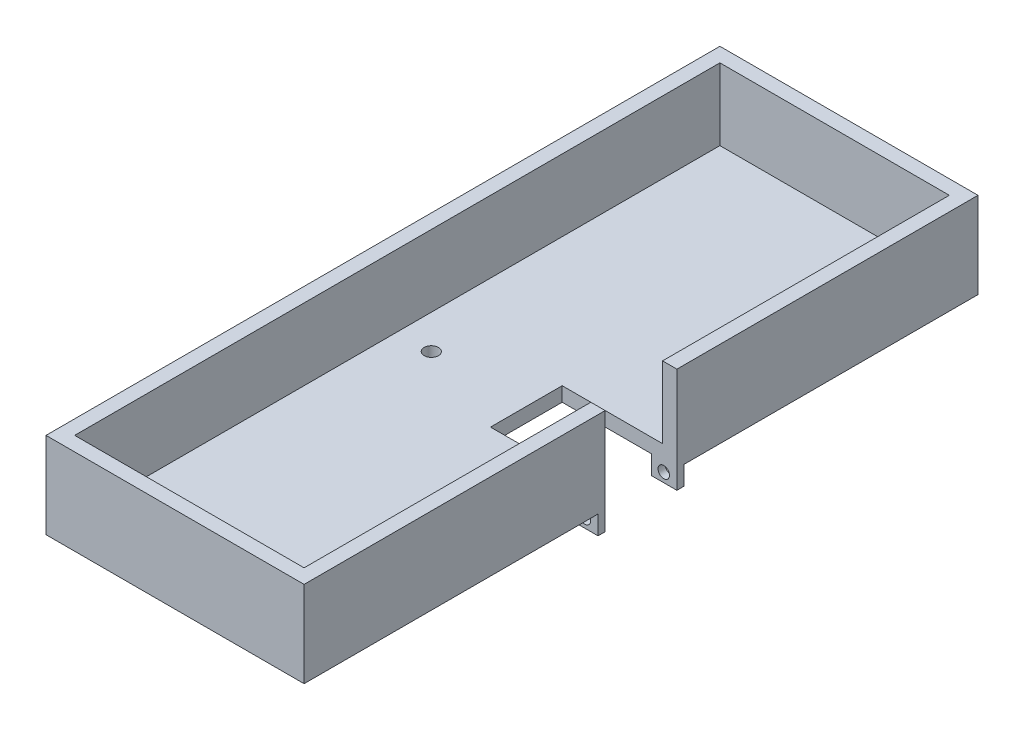
SolidWorks part; units mm, degrees
ref_plane "Front Plane" through (0, 0, 0) normal (0, 0, 1) x (1, 0, 0)
ref_plane "Top Plane" through (0, 0, 0) normal (0, 1, 0) x (1, 0, 0)
ref_plane "Right Plane" through (0, 0, 0) normal (1, 0, 0) x (0, 0, -1)
sketch "Sketch1" plane through (0, 0, 0) normal (0, 0, 1) x (1, 0, 0)
  line L0 (0, 0) -> (0, -60)
  line L1 (0, -60) -> (180, -60)
  line L2 (10, 0) -> (10, -50)
  line L3 (10, -50) -> (180, -50)
  line L4 (0, 0) -> (10, 0)
  line L5 (10, 0) -> (12.3162, 0.7131)
  line L6 (180, -50) -> (180, -60)
  dimension "D1" = 60
  dimension "D2" = 180
  dimension "D3" = 10
extrude "Boss-Extrude1" add sketch "Sketch1" along normal blind 470 contours L6 L3 L2 L4 L0 L1
sketch "Sketch2" plane through (0, -50, 0) normal (0, 1, 0) x (1, 0, 0)
  line L0 (10, -470) -> (10, 0) construction
  circle A0 centre (33.75, -235) radius 5
  dimension "D1" = 23.75
extrude "Cut-Extrude1" cut sketch "Sketch2" against normal through all
sketch "Sketch3" plane through (0, -50, 0) normal (0, 1, 0) x (1, 0, 0)
  line L0 (180, -470) -> (180, 0) construction
  line L1 (10, -470) -> (180, -470)
  line L2 (10, -470) -> (10, -460)
  line L3 (10, -460) -> (180, -460)
  line L4 (180, -470) -> (180, -460)
  line L5 (10, 0) -> (180, 0) construction
  line L6 (180, -470) -> (170, -470)
  line L7 (180, -470) -> (180, 0)
  line L8 (180, 0) -> (170, 0)
  line L9 (170, -470) -> (170, 0)
  line L11 (10, 0) -> (180, 0)
  line L12 (10, 0) -> (10, -10)
  line L13 (10, -10) -> (180, -10)
  line L14 (180, 0) -> (180, -10)
  line M2 (180, 0) -> (10, 0)
  line M3 (10, 0) -> (10, -470)
  line M4 (10, -470) -> (180, -470)
  line M5 (180, -470) -> (180, 0)
  dimension "D1" = 10
  dimension "D2" = 10
  dimension "D3" = 10
extrude "Boss-Extrude2" add sketch "Sketch3" along normal up to surface (50 mm away) contours L13 L9 M3 M2 | L9 L13 L7 M2 | L13 L9 L3 M5 | L9 L1 L3 M5 | L9 L3 M4 M3 up to face at (5, 0, 235)
sketch "Sketch4" plane through (0, -50, 0) normal (0, 1, 0) x (1, 0, 0)
  line L0 (180, -235) -> (0, -235)
  line L1 (180, -470) -> (180, 0) construction
  line L2 (0, -470) -> (0, 0) construction
  line L4 (100, -210) -> (180, -210)
  line L5 (100, -210) -> (100, -260)
  line L6 (100, -260) -> (180, -260)
  line L7 (180, -210) -> (180, -260)
  line M6 (170, -460) -> (170, -10)
  dimension "D1" = 50
  dimension "D2" = 25
  dimension "D3" = 80
extrude "Cut-Extrude2" cut sketch "Sketch4" against normal mid plane 160 contours L4 L5 L0 M6 | L5 L6 L0 M6 | L7 L4 L0 M6 | L7 L0 L6 M6
sketch "Sketch6" plane through (0, 0, 210) normal (0, 0, 1) x (1, 0, 0)
  line L0 (0, -60) -> (180, -60) construction
  line L1 (162.3438, -60) -> (180, -60)
  line L2 (162.3438, -60) -> (162.3438, -73.2021)
  line L3 (162.3438, -73.2021) -> (180, -73.2021)
  line L4 (180, -60) -> (180, -73.2021)
  circle A0 centre (170.8382, -66.7449) radius 4
extrude "Boss-Extrude3" add sketch "Sketch6" against normal blind 5
ref_plane "Plane1" through (0, 0, 235) normal (0, 0, 1) x (1, 0, 0)
mirror "Mirror1" about plane through (0, 0, 235) normal (0, 0, 1) of "Boss-Extrude3"
